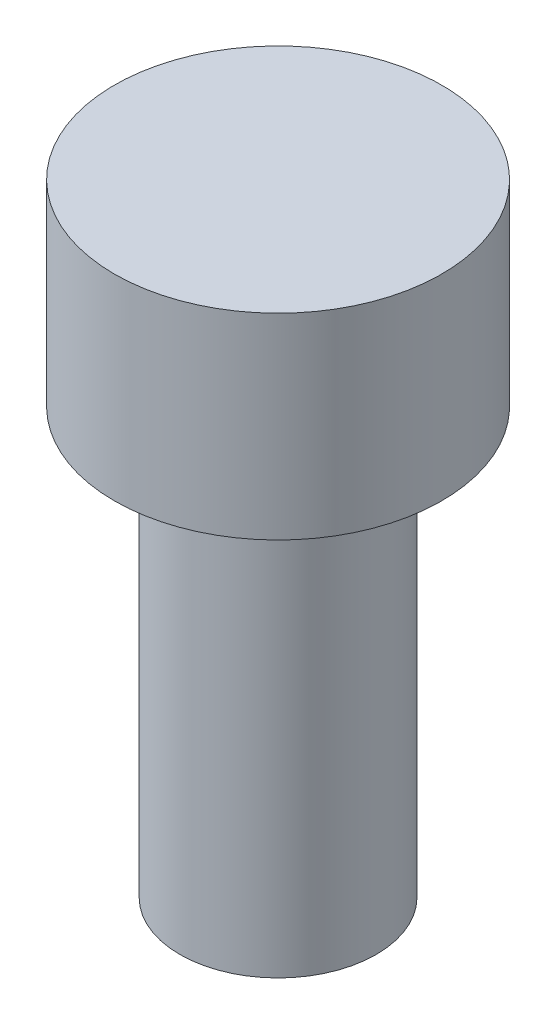
SolidWorks part; units mm, degrees
ref_plane "前视基准面" through (0, 0, 0) normal (0, 0, 1) x (1, 0, 0)
ref_plane "上视基准面" through (0, 0, 0) normal (0, 1, 0) x (1, 0, 0)
ref_plane "右视基准面" through (0, 0, 0) normal (1, 0, 0) x (0, 0, -1)
other "Configuration Table"
sketch "草图1" plane through (0, 0, 0) normal (0, 1, 0) x (1, 0, 0)
  circle A0 centre (0, 0) radius 3
  dimension "D1" = 6
extrude "凸台-拉伸1" add sketch "草图1" along normal blind 13
sketch "草图2" plane through (0, 13, 0) normal (0, 1, 0) x (1, 0, 0)
  circle A0 centre (0, 0) radius 5
  dimension "D1" = 10
extrude "凸台-拉伸2" add sketch "草图2" along normal blind 6
